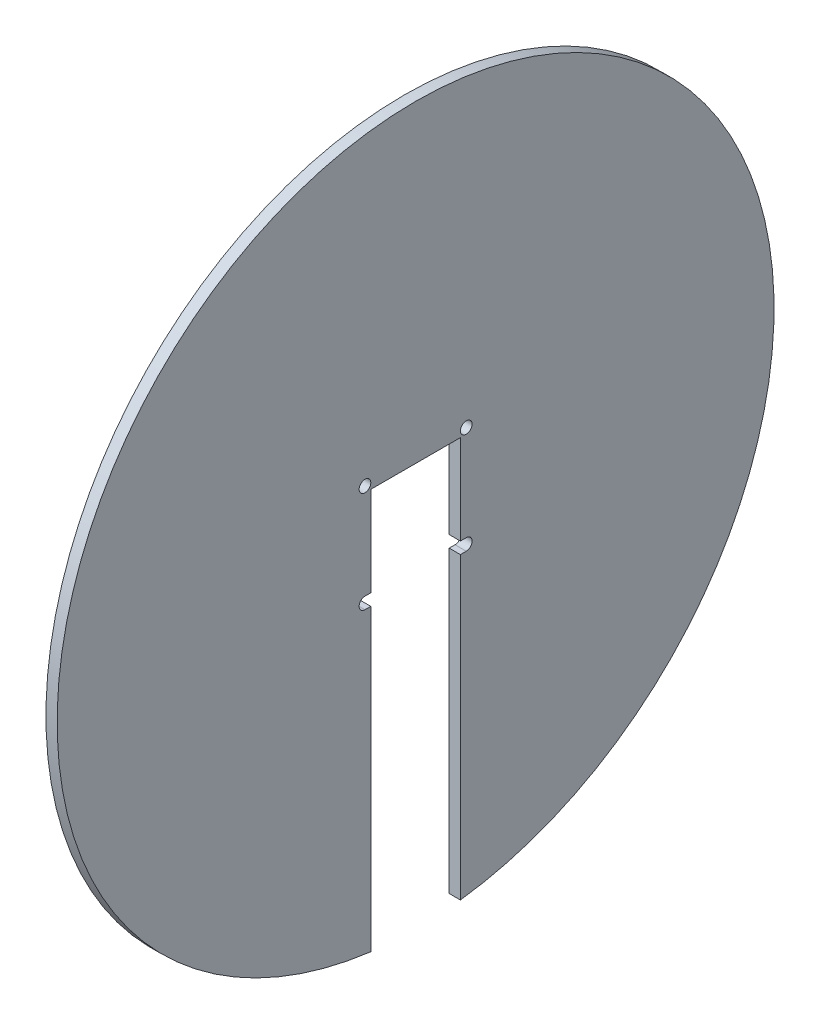
SolidWorks part; units mm, degrees
ref_plane "Front Plane" through (0, 0, 0) normal (0, 0, 1) x (1, 0, 0)
ref_plane "Top Plane" through (0, 0, 0) normal (0, 1, 0) x (1, 0, 0)
ref_plane "Right Plane" through (0, 0, 0) normal (1, 0, 0) x (0, 0, -1)
sketch "Sketch1" plane through (0, 0, 0) normal (1, 0, 0) x (0, 0, -1)
  line L1 (-12.7, 12.7) -> (12.7, 12.7)
  line L2 (-12.7, 12.7) -> (-12.7, -12.7)
  line L4 (12.7, 12.7) -> (12.7, -12.7)
  line L5 (-12.7, 12.7) -> (12.7, -12.7) construction
  line L6 (-12.7, -12.7) -> (12.7, 12.7) construction
  line L7 (-14.351, -14.351) -> (14.351, -14.351) construction
  line L8 (-14.351, -14.351) -> (-14.351, 14.351) construction
  line L9 (-14.351, 14.351) -> (14.351, 14.351) construction
  line L10 (14.351, -14.351) -> (14.351, 14.351) construction
  line L11 (-14.351, -14.351) -> (14.351, 14.351) construction
  line L12 (-14.351, 14.351) -> (14.351, -14.351) construction
  line L14 (12.7, -100.8031) -> (12.7, -16.0087)
  line L15 (-14.351, -14.351) -> (14.351, -14.351) construction
  line L16 (-14.351, -12.6933) -> (-12.6933, -12.6933)
  line L17 (-14.351, -16.0087) -> (-12.7, -16.0087)
  line L18 (-12.7, -16.0087) -> (-12.7, -100.8031)
  line L19 (12.6933, -12.6933) -> (14.351, -12.6933)
  line L20 (12.7, -16.0087) -> (14.351, -16.0087)
  arc A0 (12.7, -100.8031) -> (-12.7, -100.8031) centre (0, 0) ccw
  circle A1 centre (-14.351, 14.351) radius 1.651
  circle A2 centre (14.351, 14.351) radius 1.651
  arc A5 (-14.351, -12.6933) -> (-14.351, -16.0087) centre (-14.351, -14.351) ccw
  arc A6 (14.351, -16.0087) -> (14.351, -12.6933) centre (14.351, -14.351) ccw
  point P1 (0, -14.351)
  dimension "D1" = 203.2
  dimension "D4" = 3.302
  dimension "D2" = 25.4
  dimension "D3" = 28.702
  dimension "D5" = 25.4
extrude "Boss-Extrude1" add sketch "Sketch1" along normal blind 3.175 contours A6 L20 L14 A0 L18 L17 A5 L16 L2 L1 L4 L19 A2 A1
